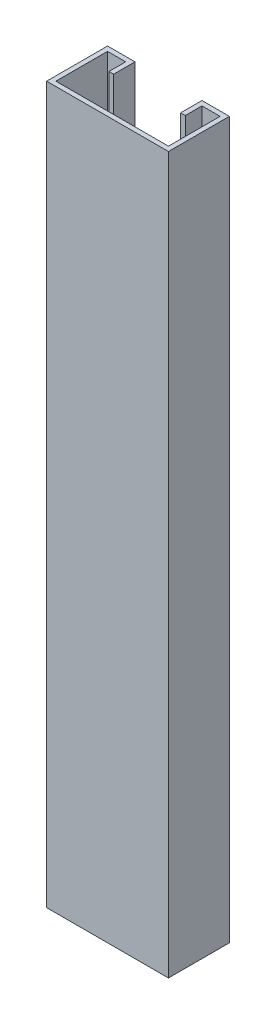
SolidWorks part; units mm, degrees
ref_plane "Alzado" through (0, 0, 0) normal (0, 0, 1) x (1, 0, 0)
ref_plane "Planta" through (0, 0, 0) normal (0, 1, 0) x (1, 0, 0)
ref_plane "Vista lateral" through (0, 0, 0) normal (1, 0, 0) x (0, 0, -1)
sketch "Croquis4" plane through (0, 0, 0) normal (0, 1, 0) x (1, 0, 0)
  line L0 (0, 0) -> (0, 7)
  line L1 (0, 7) -> (-9, 7)
  line L2 (-9, 7) -> (-9, -13)
  line L3 (-9, -13) -> (31, -13)
  line L4 (31, -13) -> (31, 7)
  line L5 (31, 7) -> (22, 7)
  line L6 (22, 7) -> (22, 0)
  line L7 (-1.52, 0) -> (-1.52, 5.48)
  line L8 (-1.52, 5.48) -> (-7.48, 5.48)
  line L9 (-7.48, 5.48) -> (-7.48, -11.48)
  line L10 (-7.48, -11.48) -> (29.48, -11.48)
  line L11 (29.48, -11.48) -> (29.48, 5.48)
  line L12 (29.48, 5.48) -> (23.52, 5.48)
  line L13 (23.52, 5.48) -> (23.52, 0)
  line L14 (-1.52, 0) -> (0, 0)
  line L15 (22, 0) -> (23.52, 0)
  dimension "D1" = 7
  dimension "D2" = 9
  dimension "D3" = 20
  dimension "D4" = 40
  dimension "D5" = 20
  dimension "D6" = 9
  dimension "D7" = 7
  dimension "D8" = 1.52
extrude "Saliente-Extruir4" add sketch "Croquis4" along normal blind 235
